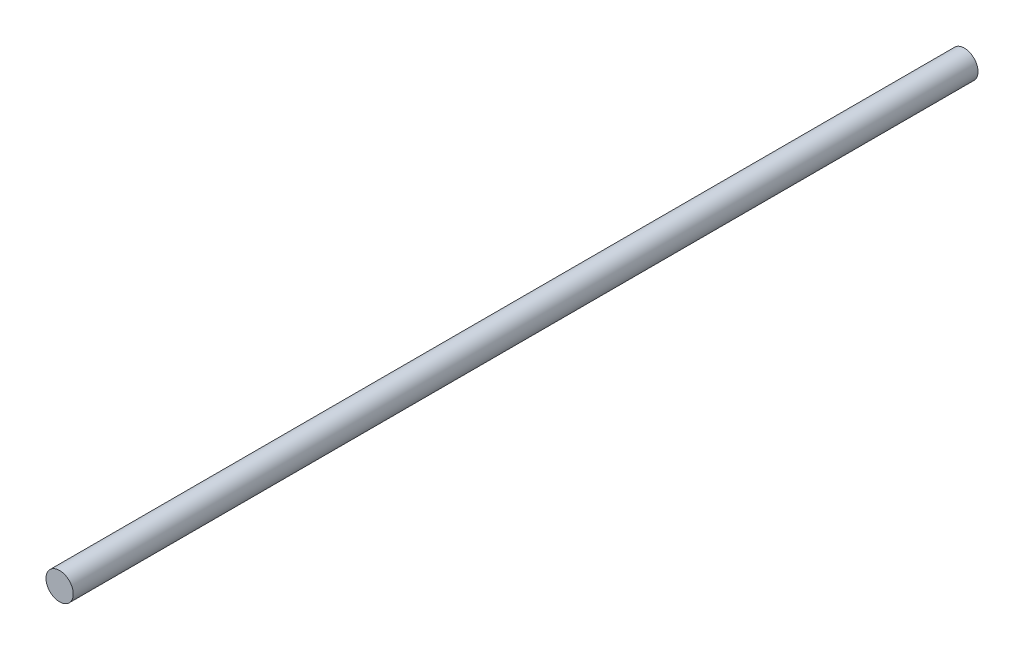
SolidWorks part; units mm, degrees
material "Nylon 101"
ref_plane "Front Plane" through (0, 0, 0) normal (0, 0, 1) x (1, 0, 0)
ref_plane "Top Plane" through (0, 0, 0) normal (0, 1, 0) x (1, 0, 0)
ref_plane "Right Plane" through (0, 0, 0) normal (1, 0, 0) x (0, 0, -1)
sketch "Sketch1" plane through (0, 0, 0) normal (0, 0, 1) x (1, 0, 0)
  circle A0 centre (0, 0) radius 6.5
extrude "Boss-Extrude1" add sketch "Sketch1" along normal blind 431.8
